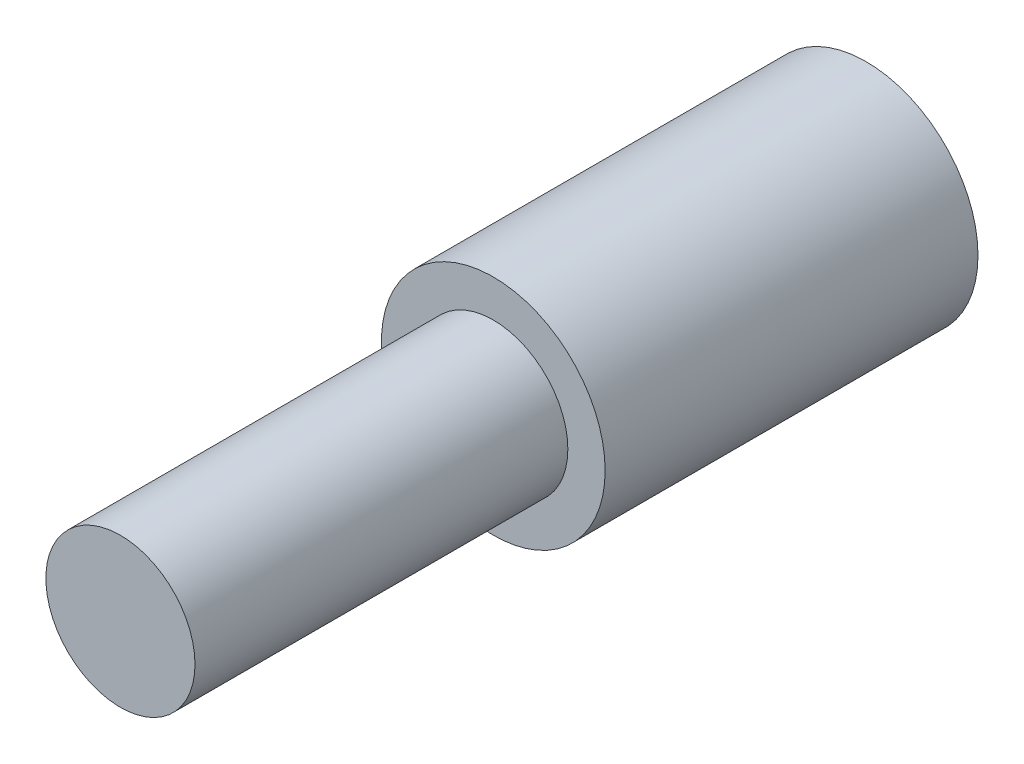
SolidWorks part; units mm, degrees
ref_plane "Front Plane" through (0, 0, 0) normal (0, 0, 1) x (1, 0, 0)
ref_plane "Top Plane" through (0, 0, 0) normal (0, 1, 0) x (1, 0, 0)
ref_plane "Right Plane" through (0, 0, 0) normal (1, 0, 0) x (0, 0, -1)
sketch "Sketch1" plane through (0, 0, 0) normal (0, 0, 1) x (1, 0, 0)
  circle A0 centre (0, 0) radius 3
extrude "Boss-Extrude1" add sketch "Sketch1" along normal blind 10
sketch "Sketch2" plane through (0, 0, 10) normal (0, 0, 1) x (1, 0, 0)
  circle A0 centre (0, 0) radius 2
extrude "Boss-Extrude2" add sketch "Sketch2" along normal blind 10
